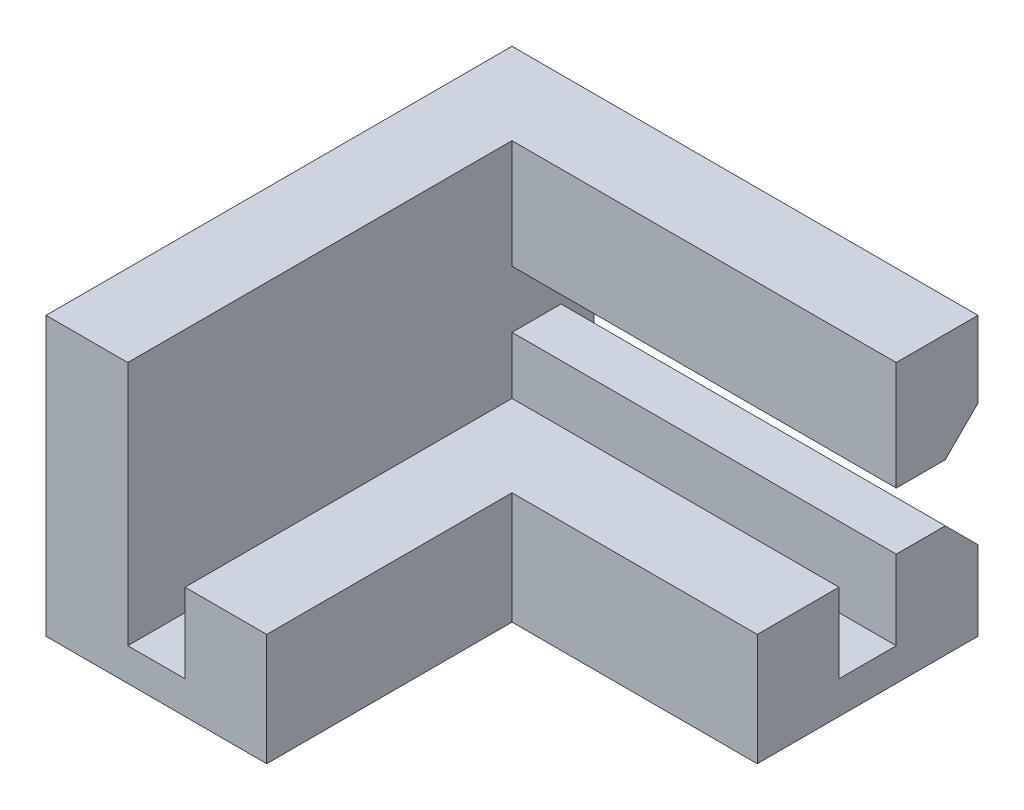
SolidWorks part; units mm, degrees
ref_plane "Front Plane" through (0, 0, 0) normal (0, 0, 1) x (1, 0, 0)
ref_plane "Top Plane" through (0, 0, 0) normal (0, 1, 0) x (1, 0, 0)
ref_plane "Right Plane" through (0, 0, 0) normal (1, 0, 0) x (0, 0, -1)
sketch "Sketch1" plane through (0, 0, 0) normal (0, 1, 0) x (1, 0, 0)
  line L0 (0, 4.3917) -> (0, 0.8917)
  line L1 (0, 0.8917) -> (15, 0.8917)
  line L2 (15, 0.8917) -> (15, -14.1083)
  line L3 (15, -14.1083) -> (18.5, -14.1083)
  line L4 (18.5, -14.1083) -> (18.5, 4.3917)
  line L5 (18.5, 4.3917) -> (0, 4.3917)
  line L6 (23.5, 9.3917) -> (-5, 9.3917)
  line L7 (-5, 9.3917) -> (-5, -4.1083)
  line L8 (-5, -4.1083) -> (10, -4.1083)
  line L9 (10, -4.1083) -> (10, -19.1083)
  line L10 (10, -19.1083) -> (23.5, -19.1083)
  line L11 (23.5, -19.1083) -> (23.5, 9.3917)
  dimension "D1" = 3.5
  dimension "D2" = 3.5
  dimension "D3" = 15
  dimension "D4" = 15
  dimension "D5" = 5
extrude "Boss-Extrude1" add sketch "Sketch1" along normal blind 15
sketch "Sketch2" plane through (0, 0, 0) normal (0, -1, 0) x (1, 0, 0)
  line L0 (-5, 4.1083) -> (10, 4.1083)
  line L1 (10, 4.1083) -> (10, 19.1083)
  line L2 (10, 19.1083) -> (23.5, 19.1083)
  line L3 (23.5, 19.1083) -> (23.5, -9.3917)
  line L4 (23.5, -9.3917) -> (-5, -9.3917)
  line L5 (-5, -9.3917) -> (-5, 4.1083)
extrude "Boss-Extrude2" add sketch "Sketch2" along normal blind 2
sketch "Sketch3" plane through (0, 15, 0) normal (0, 1, 0) x (1, 0, 0)
  line L0 (18.5, 4.3917) -> (-5, 4.3917)
  line L1 (-5, 9.3917) -> (-5, -4.1083) construction
  line L2 (-5, 4.3917) -> (-5, 0.8917)
  line L5 (15, -19.1083) -> (18.5, -19.1083)
  line L6 (18.5, -19.1083) -> (18.5, 4.3917)
  line L7 (18.5, -14.1083) -> (18.5, 4.3917) construction
  line L9 (10, -19.1083) -> (23.5, -19.1083) construction
  line L10 (-5, 0.8917) -> (-5, -4.1083)
  line L11 (-5, -4.1083) -> (10, -4.1083)
  line L12 (10, -4.1083) -> (10, -19.1083)
  line L13 (10, -19.1083) -> (15, -19.1083)
extrude "Cut-Extrude1" cut sketch "Sketch3" against normal offset from surface (10.15 mm away) 4.85 up to face at (11.1667, 0, 2.9416)
sketch "Sketch4" plane through (0, 4.85, 0) normal (0, 1, 0) x (1, 0, 0)
  line L0 (-5, 4.3917) -> (18.5, 4.3917)
  line L1 (18.5, 4.3917) -> (18.5, -19.1083)
  line L2 (18.5, -19.1083) -> (15, -19.1083)
  line L3 (18.5, -19.1083) -> (10, -19.1083) construction
  line L4 (15, -19.1083) -> (15, 0.8917)
  line L5 (15, 0.8917) -> (-5, 0.8917)
  line L6 (-5, 0.8917) -> (-5, 4.3917)
  line L7 (0, 0.8917) -> (15, 0.8917) construction
  line L8 (15, 0.8917) -> (15, -14.1083) construction
extrude "Cut-Extrude2" cut sketch "Sketch4" against normal up to surface (4.85 mm away) up to face at (11.1667, 0, 2.9416)
sketch "Sketch5" plane through (0, 0, -4.3917) normal (0, 0, 1) x (1, 0, 0)
  line L0 (-5, 4.85) -> (18.5, 4.85)
  line L1 (18.5, 15) -> (18.5, 0) construction
  line L2 (18.5, 4.85) -> (18.5, 8.35)
  line L3 (18.5, 8.35) -> (-10.7412, 8.35)
  line L4 (-10.7412, 8.35) -> (-10.7412, 4.85)
  line L5 (-10.7412, 4.85) -> (-5, 4.85)
  dimension "D1" = 3.5
extrude "Cut-Extrude5" cut sketch "Sketch5" against normal through all both and the other way through all
chamfer "Chamfer3" distance 2 angle 45 2 edges at (6.75, 4.85, -9.3917) (6.75, 8.35, -9.3917)
ref_plane "Plane1" through (-15, 0, 0) normal (-1, 0, 0) x (0, 0, 1)
mirror "Mirror1" about plane through (-15, 0, 0) normal (-1, 0, 0) of bodies 107
sketch "Sketch6" plane through (0, 15, 0) normal (0, 1, 0) x (1, 0, 0)
  line L1 (-9.8515, -25.29) -> (29.8515, -25.29)
  line L2 (-9.8515, -25.29) -> (-9.8515, 17.0734)
  line L3 (-9.8515, 17.0734) -> (29.8515, 17.0734)
  line L4 (29.8515, -25.29) -> (29.8515, 17.0734)
  line L5 (-9.8515, -25.29) -> (29.8515, 17.0734) construction
  line L6 (-9.8515, 17.0734) -> (29.8515, -25.29) construction
  point P0 (10, -4.1083)
extrude "Cut-Extrude6" cut sketch "Sketch6" against normal through all both and the other way through all
